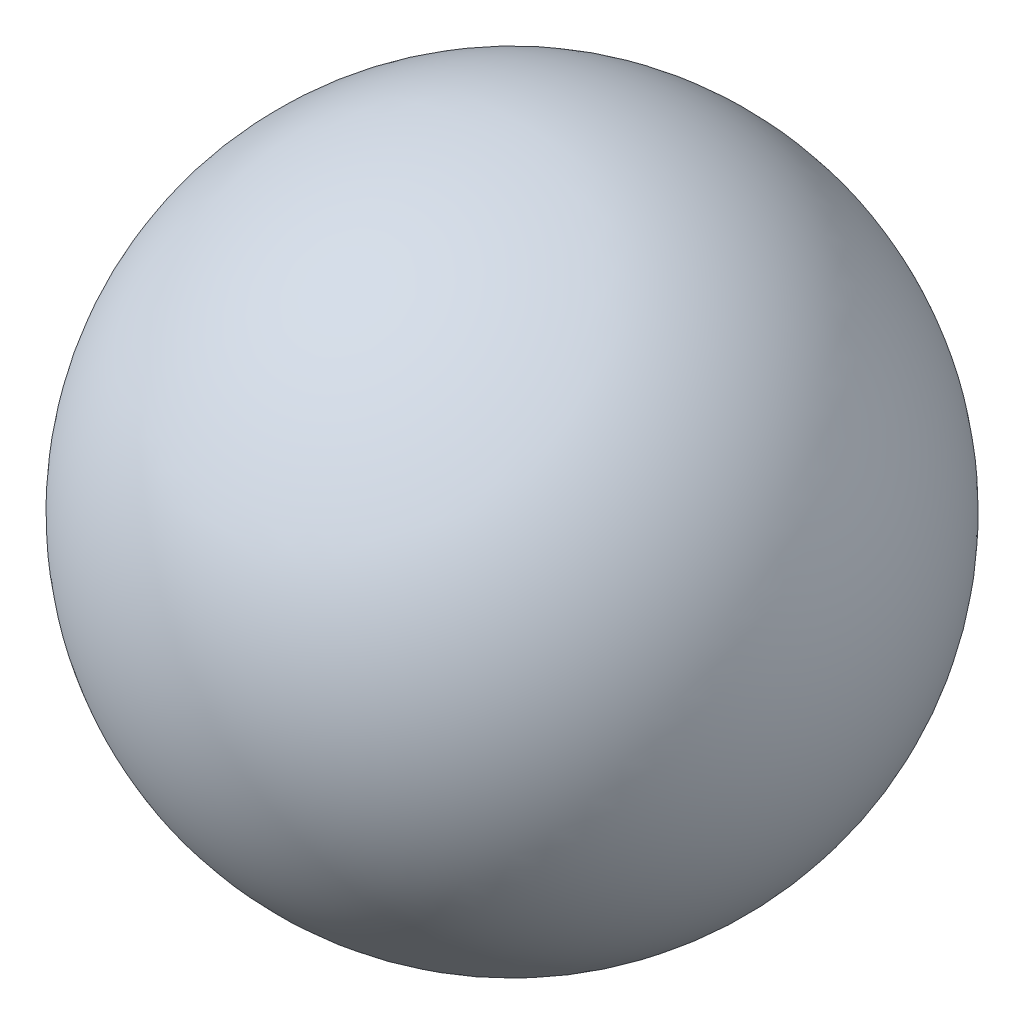
SolidWorks part; units mm, degrees
ref_plane "Front Plane" through (0, 0, 0) normal (0, 0, 1) x (1, 0, 0)
ref_plane "Top Plane" through (0, 0, 0) normal (0, 1, 0) x (1, 0, 0)
ref_plane "Right Plane" through (0, 0, 0) normal (1, 0, 0) x (0, 0, -1)
sketch "Sketch1" plane through (0, 0, 0) normal (0, 1, 0) x (1, 0, 0)
  line L0 (0, 0) -> (0, 15) construction
  line L1 (0, 0) -> (7.737, 0) construction
  line L2 (0, -15) -> (0, 15)
  arc A1 (0, 15) -> (0, -15) centre (0, 0) cw
  dimension "D1" = 15
revolve "Revolve9" add sketch "Sketch1" angle 360 about L2
